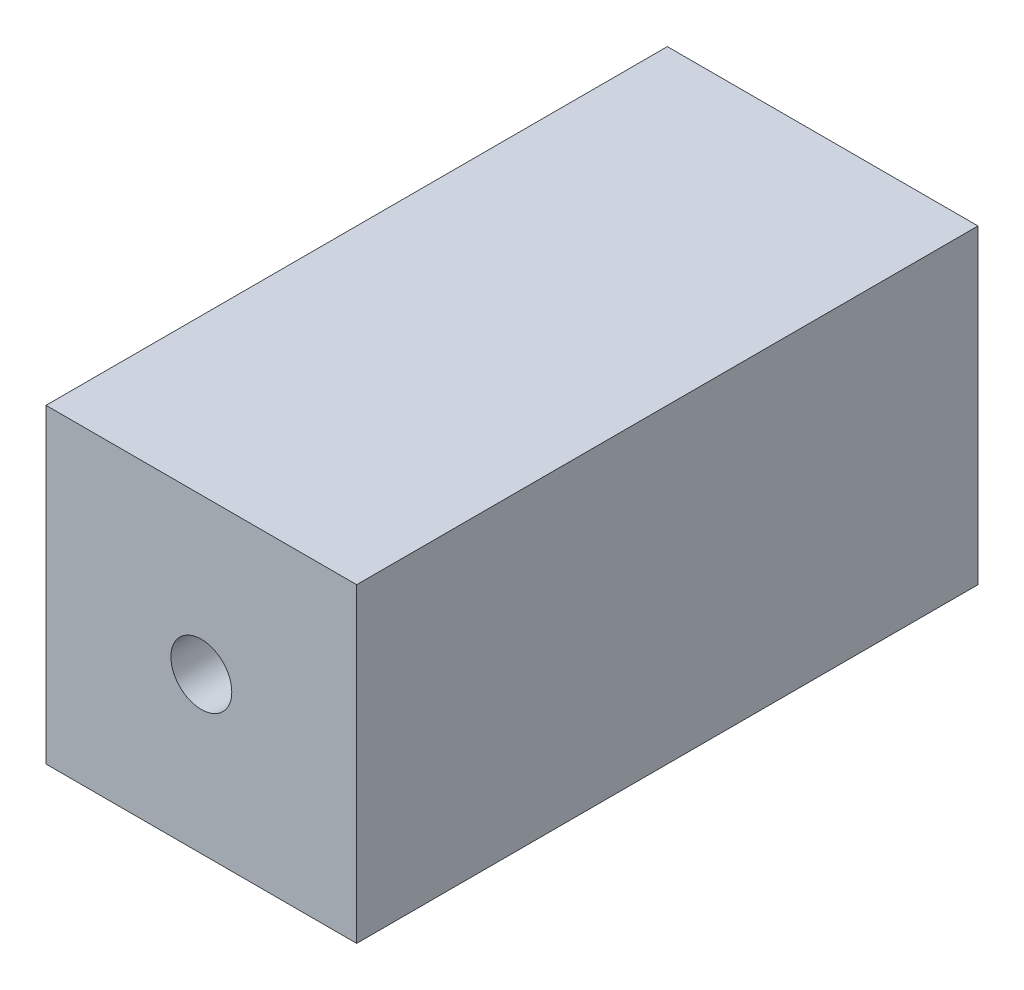
SolidWorks part; units mm, degrees
ref_plane "Front Plane" through (0, 0, 0) normal (0, 0, 1) x (1, 0, 0)
ref_plane "Top Plane" through (0, 0, 0) normal (0, 1, 0) x (1, 0, 0)
ref_plane "Right Plane" through (0, 0, 0) normal (1, 0, 0) x (0, 0, -1)
sketch "Sketch1" plane through (0, 0, 0) normal (0, 0, 1) x (1, 0, 0)
  line L1 (0, 0) -> (25.4, 0)
  line L2 (0, 0) -> (0, 25.4)
  line L3 (0, 25.4) -> (25.4, 25.4)
  line L4 (25.4, 0) -> (25.4, 25.4)
  dimension "D1" = 25.4
  dimension "D2" = 25.4
extrude "Boss-Extrude1" add sketch "Sketch1" along normal blind 50.8
sketch "Sketch2" plane through (0, 0, 50.8) normal (0, 0, 1) x (1, 0, 0)
  line L0 (25.4, 25.4) -> (0, 25.4) construction
  line L1 (25.4, 0) -> (25.4, 25.4) construction
  circle A0 centre (12.7, 12.7) radius 2.4892
  dimension "D1" = 4.9784
  dimension "D2" = 12.7
  dimension "D3" = 12.7
extrude "Cut-Extrude1" cut sketch "Sketch2" against normal through all
